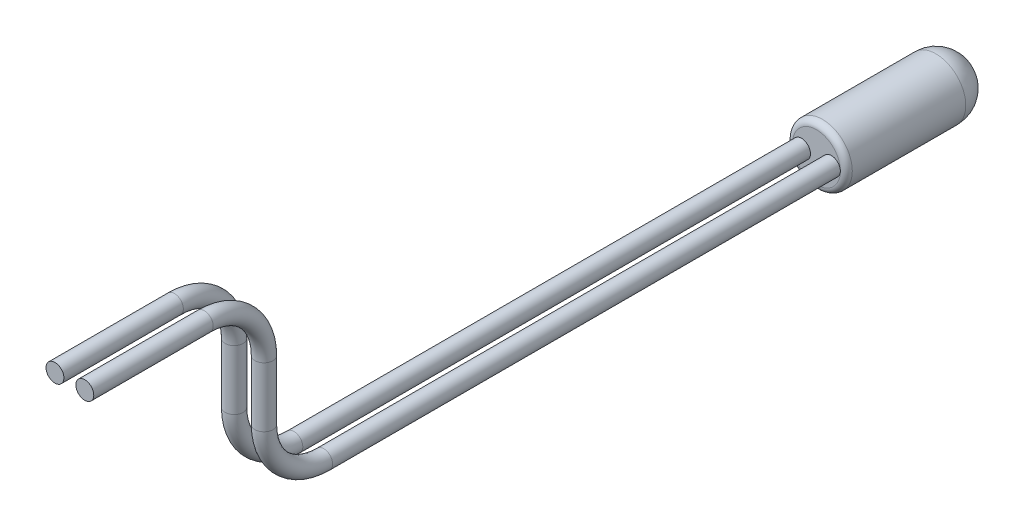
SolidWorks part; units mm, degrees
material "Glass"
ref_plane "Front Plane" through (0, 0, 0) normal (0, 0, 1) x (1, 0, 0)
ref_plane "Top Plane" through (0, 0, 0) normal (0, 1, 0) x (1, 0, 0)
ref_plane "Right Plane" through (0, 0, 0) normal (1, 0, 0) x (0, 0, -1)
sketch "Sketch2" plane through (0, 0, 0) normal (0, 1, 0) x (1, 0, 0)
  line L0 (0, 1.25) -> (0, -1.25)
  line L2 (0, -1.25) -> (-0.5, -1.25)
  line L3 (-0.5, 0.75) -> (-0.5, -1.25)
  arc A0 (0, 1.25) -> (-0.5, 0.75) centre (0, 0.75) ccw
  dimension "D1" = 0.5
  dimension "D2" = 2.5
revolve "Revolve1" add sketch "Sketch2" angle 360 about L0
fillet "Fillet2" radius 0.1 1 edges at (-0.5, 0, 1.25)
sketch "Sketch3" plane through (0, 0, 1.25) normal (0, 0, 1) x (1, 0, 0)
  line L0 (-0.9081, 0) -> (0.9972, 0) construction
  line L1 (0, 0.1251) -> (0, 2.0304) construction
  circle A0 centre (-0.25, 0) radius 0.15
  circle A1 centre (0.25, 0) radius 0.15
  dimension "D2" = 0.3
  dimension "D1" = 0.5
sketch "Sketch4" plane through (0, 0, 0) normal (1, 0, 0) x (0, 0, -1)
  line L5 (-1.25, 0) -> (-9.75, 0)
  line L6 (-1.25, 0.15) -> (-1.25, -0.15) construction
  line L7 (-10.75, 1) -> (-10.75, 2)
  line L8 (-11.75, 3) -> (-13.75, 3)
  arc A0 (-10.75, 1) -> (-9.75, 0) centre (-9.75, 1) ccw
  arc A1 (-10.75, 2) -> (-11.75, 3) centre (-11.75, 2) ccw
  dimension "D1" = 1
  dimension "D3" = 1
  dimension "D2" = 1
  dimension "D4" = 8.5
  dimension "D5" = 2
sweep "Sweep1" add profiles "Sketch3" path "Sketch4"
